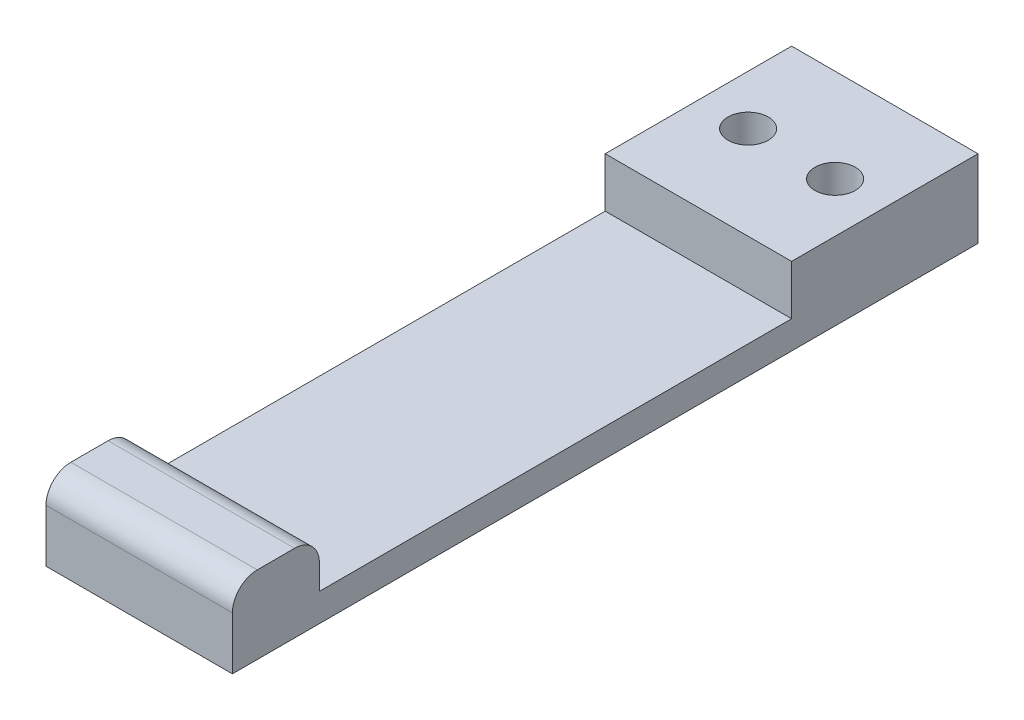
SolidWorks part; units mm, degrees
ref_plane "Front Plane" through (0, 0, 0) normal (0, 0, 1) x (1, 0, 0)
ref_plane "Top Plane" through (0, 0, 0) normal (0, 1, 0) x (1, 0, 0)
ref_plane "Right Plane" through (0, 0, 0) normal (1, 0, 0) x (0, 0, -1)
sketch "Sketch1" plane through (0, 0, 0) normal (1, 0, 0) x (0, 0, -1)
  line L1 (0, 2.25) -> (60, 2.25)
  line L2 (0, 2.25) -> (0, 0)
  line L3 (0, 0) -> (60, 0)
  line L4 (60, 2.25) -> (60, 0)
  line L6 (0, 2.25) -> (0, 4.25)
  line L7 (2, 6.25) -> (5, 6.25)
  line L8 (7, 2.25) -> (7, 4.25)
  line L10 (60, 2.25) -> (60, 6.25)
  line L11 (60, 6.25) -> (45, 6.25)
  line L12 (45, 2.25) -> (45, 6.25)
  arc A0 (5, 6.25) -> (7, 4.25) centre (5, 4.25) cw
  arc A1 (0, 4.25) -> (2, 6.25) centre (2, 4.25) cw
  point P15 (7, 6.25)
  point P18 (0, 6.25)
  dimension "D7" = 2
  dimension "D1" = 2.25
  dimension "D2" = 4
  dimension "D3" = 60
  dimension "D4" = 15
  dimension "D5" = 7
  dimension "D6" = 4
extrude "Boss-Extrude1" add sketch "Sketch1" along normal blind 15 contours L4 L1 L2 L3 | L1 L8 L7 L6 | L12 L1 L10 L11
sketch "Sketch2" plane through (0, 0, 0) normal (0, -1, 0) x (1, 0, 0)
  line L0 (-20.7004, -52.5) -> (40.88, -52.5) construction
  line L1 (15, -60) -> (0, -60) construction
  line L2 (0, 0) -> (0, -60) construction
  line L3 (15, 0) -> (15, -60) construction
  circle A0 centre (11, -52.5) radius 1.625
  circle A1 centre (4, -52.5) radius 1.625
  dimension "D2" = 3.25
  dimension "D3" = 3.25
  dimension "D1" = 7.5
  dimension "D4" = 4
  dimension "D5" = 4
extrude "Cut-Extrude1" cut sketch "Sketch2" against normal up to surface (6.25 mm away) up to face at (7.5, 6.25, -52.5)
